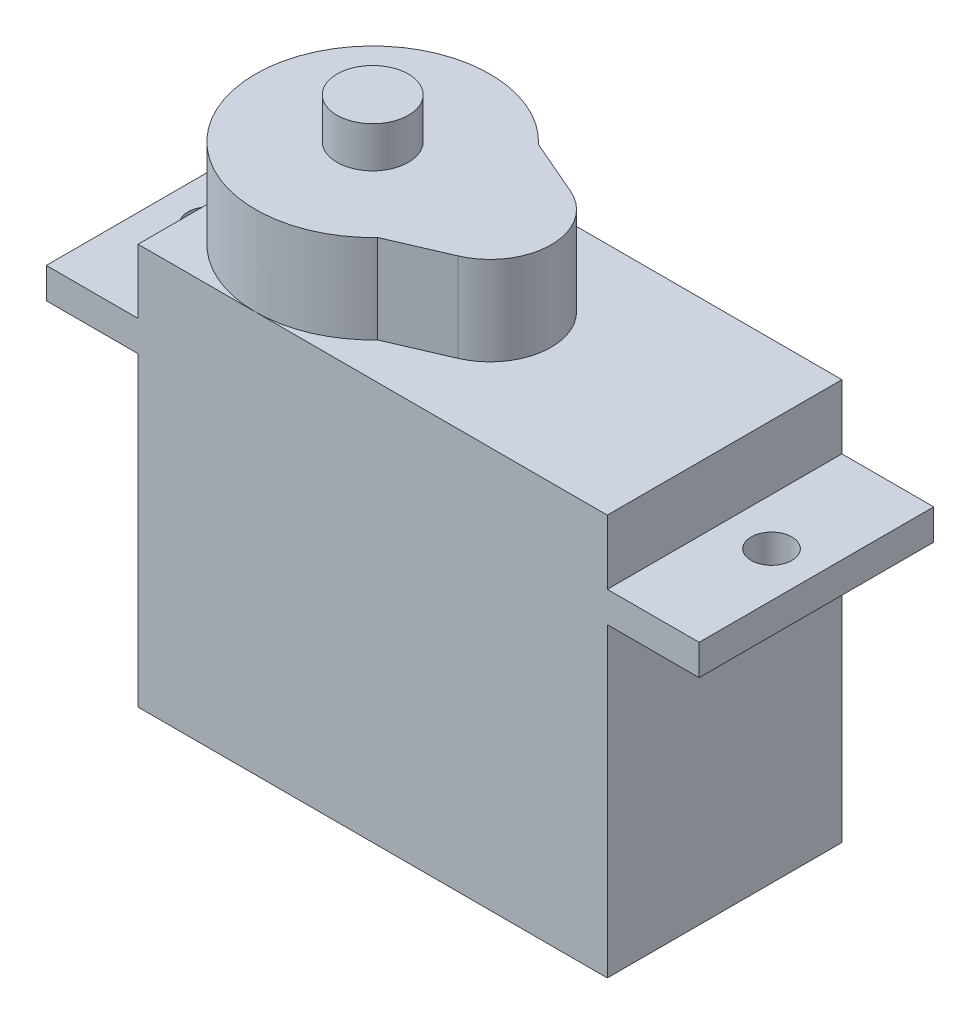
SolidWorks part; units mm, degrees
ref_plane "前视基准面" through (0, 0, 0) normal (0, 0, 1) x (1, 0, 0)
ref_plane "上视基准面" through (0, 0, 0) normal (0, 1, 0) x (1, 0, 0)
ref_plane "右视基准面" through (0, 0, 0) normal (1, 0, 0) x (0, 0, -1)
other "Configuration Table"
sketch "草图1" plane through (0, 0, 0) normal (0, 1, 0) x (1, 0, 0)
  line L1 (-11.5, 5.75) -> (11.5, 5.75)
  line L2 (-11.5, 5.75) -> (-11.5, -5.75)
  line L3 (-11.5, -5.75) -> (11.5, -5.75)
  line L4 (11.5, 5.75) -> (11.5, -5.75)
  line L5 (-11.5, 5.75) -> (11.5, -5.75) construction
  line L6 (-11.5, -5.75) -> (11.5, 5.75) construction
  point P0 (0, 0)
  dimension "D1" = 11.5
  dimension "D2" = 23
extrude "凸台-拉伸1" add sketch "草图1" along normal blind 15
sketch "草图2" plane through (0, 0, 0) normal (0, 1, 0) x (1, 0, 0)
  line L1 (-16, 5.75) -> (16, 5.75)
  line L2 (-16, 5.75) -> (-16, -5.75)
  line L3 (-16, -5.75) -> (16, -5.75)
  line L4 (16, 5.75) -> (16, -5.75)
  line L5 (-16, 5.75) -> (16, -5.75) construction
  line L6 (-16, -5.75) -> (16, 5.75) construction
  point P0 (0, 0)
  dimension "D1" = 32
  dimension "D2" = 11.5
extrude "凸台-拉伸2" add sketch "草图2" along normal blind 1.5 from surface at 15 starting at face at (0, 15, 0)
sketch "草图3" plane through (0, 0, 0) normal (0, 1, 0) x (1, 0, 0)
  line L1 (-11.5, 5.75) -> (11.5, 5.75)
  line L2 (-11.5, 5.75) -> (-11.5, -5.75)
  line L3 (-11.5, -5.75) -> (11.5, -5.75)
  line L4 (11.5, 5.75) -> (11.5, -5.75)
  line L5 (-11.5, 5.75) -> (11.5, -5.75) construction
  line L6 (-11.5, -5.75) -> (11.5, 5.75) construction
  point P0 (0, 0)
  dimension "D1" = 11.5
  dimension "D2" = 23
extrude "凸台-拉伸3" add sketch "草图3" along normal blind 19.65
sketch "草图4" plane through (0, 0, 0) normal (0, 1, 0) x (1, 0, 0)
  line L0 (-13.8, 0) -> (13.8, 0) construction
  circle A0 centre (-13.8, 0) radius 1
  circle A1 centre (13.8, 0) radius 1
  point P4 (0, 0)
  dimension "D2" = 2
  dimension "D3" = 2
  dimension "D1" = 27.6
extrude "切除-拉伸1" cut sketch "草图4" along normal blind 19.65
sketch "草图5" plane through (0, 0, 0) normal (0, 1, 0) x (1, 0, 0)
  line L0 (-11.5, -5.75) -> (11.5, -5.75) construction
  line L1 (-11.5, 5.75) -> (0, 5.75) construction
  line L2 (-11.5, 5.75) -> (-11.5, -5.75) construction
  line L3 (-11.5, -5.75) -> (0, -5.75) construction
  line L4 (0, 5.75) -> (0, -5.75) construction
  line L5 (0, 5.75) -> (-11.5, -5.75) construction
  line L6 (-11.5, 5.75) -> (0, -5.75) construction
  circle A0 centre (-5.75, 0) radius 5.75
extrude "凸台-拉伸4" add sketch "草图5" along normal blind 24
sketch "草图6" plane through (0, 0, 0) normal (0, 1, 0) x (1, 0, 0)
  line L0 (-1.5652, 3.9434) -> (1.1891, 2.7543)
  line L1 (-1.5652, -3.9434) -> (1.1891, -2.7543)
  arc A0 (1.1891, -2.7543) -> (1.1891, 2.7543) centre (0, 0) ccw
  circle A1 centre (-5.75, 0) radius 5.75 construction
  arc A2 (-1.5652, 3.9434) -> (-1.5652, -3.9434) centre (-5.75, 0) ccw
  dimension "D1" = 6
extrude "凸台-拉伸5" add sketch "草图6" along normal blind 24
sketch "草图7" plane through (0, 0, 0) normal (0, 1, 0) x (1, 0, 0)
  circle A0 centre (-5.75, 0) radius 1.75
  dimension "D1" = 3.5
extrude "凸台-拉伸6" add sketch "草图7" along normal blind 2 from surface
